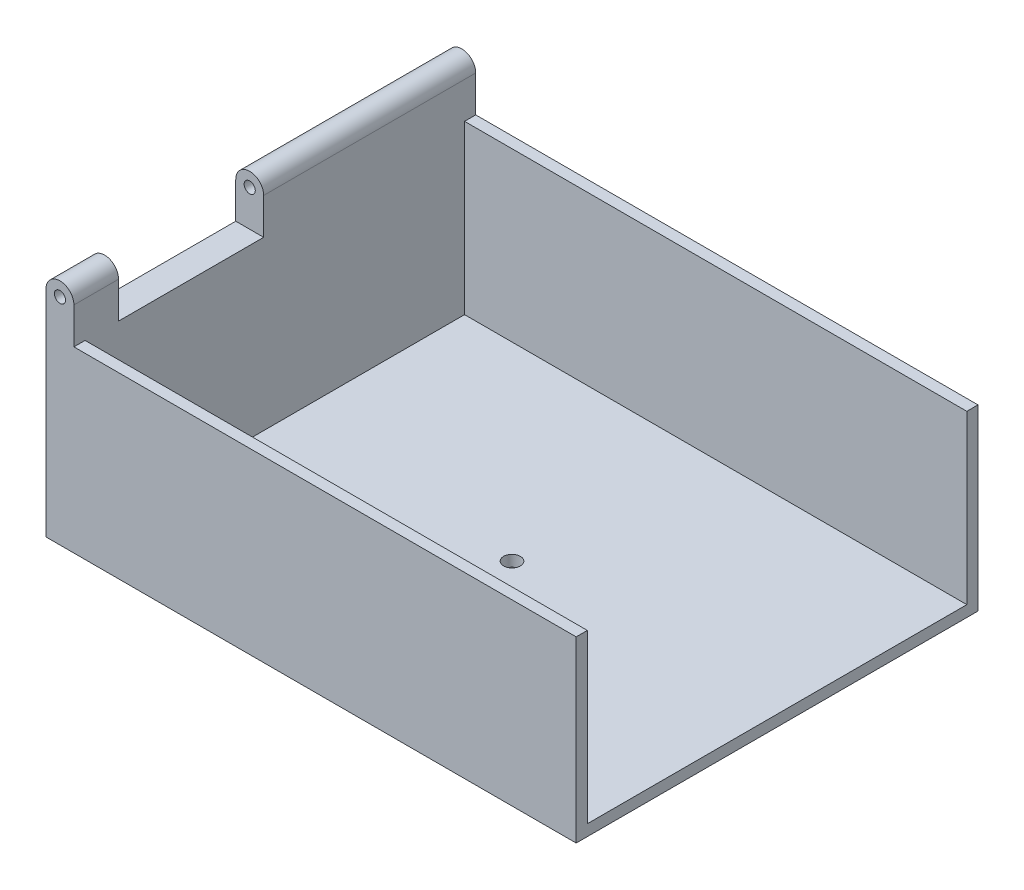
SolidWorks part; units mm, degrees
other "Markup1"
sketch "Sketch14" plane through (65.6118, 41, 65.6118) normal (0.8235, 0.5673, 0.0014) x (0.0504, -0.0708, -0.9962)
ref_plane "Front Plane" through (0, 0, 0) normal (0, 0, 1) x (1, 0, 0)
ref_plane "Top Plane" through (0, 0, 0) normal (0, 1, 0) x (1, 0, 0)
ref_plane "Right Plane" through (0, 0, 0) normal (1, 0, 0) x (0, 0, -1)
sketch "Sketch1" plane through (0, 0, 0) normal (0, 1, 0) x (1, 0, 0)
  line L1 (-47.5, -36) -> (47.5, -36)
  line L2 (-47.5, -36) -> (-47.5, 36)
  line L3 (-47.5, 36) -> (47.5, 36)
  line L4 (47.5, -36) -> (47.5, 36)
  line L5 (-47.5, -36) -> (47.5, 36) construction
  line L6 (-47.5, 36) -> (47.5, -36) construction
  point P0 (0, 0)
  dimension "D1" = 72
  dimension "D2" = 95
extrude "Boss-Extrude1" add sketch "Sketch1" along normal blind 35
sketch "Sketch5" plane through (0, 35, 0) normal (0, 1, 0) x (1, 0, 0)
  line L0 (47.5, -36) -> (47.5, 36) construction
  line L1 (-42.5, -34) -> (47.5, -34)
  line L2 (-42.5, -34) -> (-42.5, 34)
  line L3 (-42.5, 34) -> (47.5, 34)
  line L4 (47.5, -34) -> (47.5, 34)
  line L5 (-47.5, -36) -> (47.5, -36) construction
  line L7 (-47.5, 36) -> (-47.5, -36) construction
  dimension "D1" = 68
  dimension "D2" = 2
  dimension "D3" = 5
extrude "Cut-Extrude1" cut sketch "Sketch5" against normal blind 33
sketch "Sketch10" plane through (0, 0, 36) normal (0, 0, 1) x (1, 0, 0)
  line L0 (-42.5, 35) -> (-42.5, 38.5)
  line L1 (-47.5, 35) -> (47.5, 35) construction
  line L2 (-47.5, 35) -> (-47.5, 38.5)
  line L4 (-47.5, 35) -> (-42.5, 35)
  arc A0 (-42.5, 38.5) -> (-47.5, 38.5) centre (-45, 38.5) ccw
  circle A1 centre (-45, 38.5) radius 1
  dimension "D4" = 2.5
  dimension "D2" = 2
  dimension "D1" = 5
  dimension "D3" = 3.5
  dimension "D5" = 3.5
extrude "Boss-Extrude5" add sketch "Sketch10" against normal through all
sketch "Sketch16" plane through (0, 0, 0) normal (0, -1, 0) x (1, 0, 0)
  circle A0 centre (0, 0) radius 7.5
  dimension "D1" = 15
sketch "Sketch19" plane through (0, 35, 0) normal (0, 1, 0) x (1, 0, 0)
  line L0 (-42.5, 34) -> (-42.5, -34) construction
  line L1 (-42.5, -28) -> (-47.5, -28)
  line L2 (-42.5, -28) -> (-42.5, -2)
  line L3 (-42.5, -2) -> (-47.5, -2)
  line L4 (-47.5, -28) -> (-47.5, -2)
  line L5 (-47.5, 36) -> (-47.5, -36) construction
  line L6 (-42.5, -34) -> (47.5, -34) construction
  dimension "D1" = 26
  dimension "D2" = 6
extrude "Cut-Extrude2" cut sketch "Sketch19" along normal blind 10 and the other way blind 3
sketch "Sketch20" plane through (0, 35, 0) normal (0, 1, 0) x (1, 0, 0)
  line L1 (-42.5, -36) -> (47.5, -36)
  line L2 (-42.5, -36) -> (-42.5, 36)
  line L3 (-42.5, 36) -> (47.5, 36)
  line L4 (47.5, -36) -> (47.5, 36)
extrude "Cut-Extrude3" cut sketch "Sketch20" against normal blind 3
sketch "Sketch21" plane through (0, 2, 0) normal (0, 1, 0) x (1, 0, 0)
  circle A0 centre (0, 0) radius 1.5
  dimension "D1" = 3
extrude "Cut-Extrude4" cut sketch "Sketch21" against normal through all
